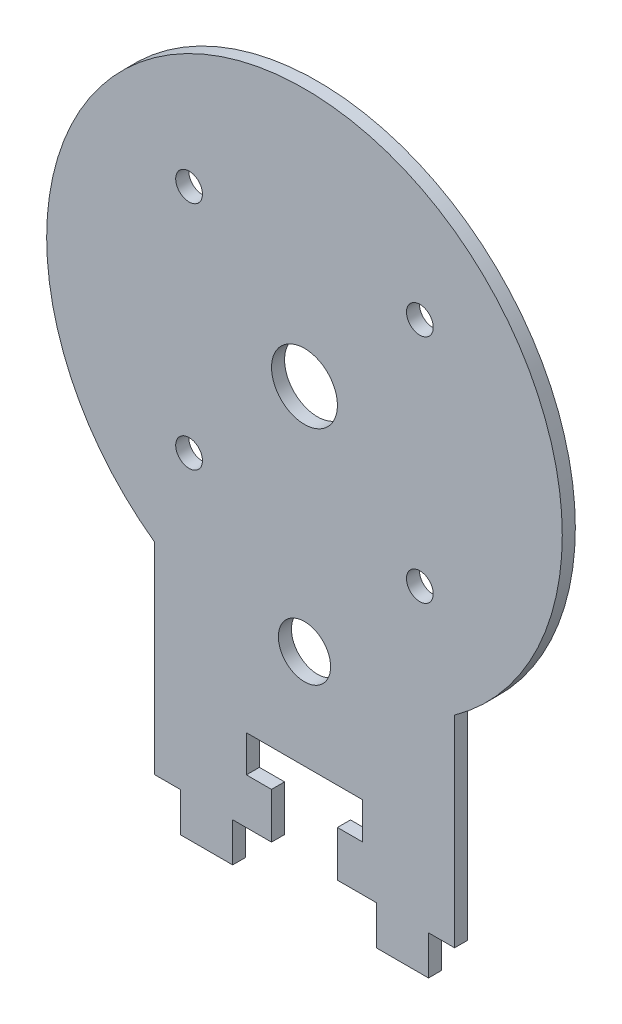
SolidWorks part; units mm, degrees
ref_plane "前视基准面" through (0, 0, 0) normal (0, 0, 1) x (1, 0, 0)
ref_plane "上视基准面" through (0, 0, 0) normal (0, 1, 0) x (1, 0, 0)
ref_plane "右视基准面" through (0, 0, 0) normal (1, 0, 0) x (0, 0, -1)
sketch "草图1" plane through (0, 0, 0) normal (0, 0, 1) x (1, 0, 0)
  line L0 (-7.6377, 83.7363) -> (-7.6377, -1.0167) construction
  line L1 (-48.6877, 98.7363) -> (33.4123, 98.7363) construction
  line L2 (-2.5877, 20.7363) -> (-2.5877, 27.7363)
  line L5 (-2.5877, 27.7363) -> (1.2623, 27.7363)
  line L6 (1.2623, 27.7363) -> (1.2623, 33.3363)
  line L10 (-7.6377, 83.7363) -> (29.2367, 46.8619) construction
  line L11 (1.2623, 33.3363) -> (-2.6877, 33.3363)
  line L15 (3.3623, 20.7363) -> (3.3623, 14.7363)
  line L16 (3.3623, 14.7363) -> (11.3623, 14.7363)
  line L17 (11.3623, 14.7363) -> (11.3623, 20.7363)
  line L18 (7.3623, 14.7363) -> (7.3623, 20.7363) construction
  line L19 (11.3623, 20.7363) -> (-2.5877, 20.7363) construction
  line L20 (-2.5877, 20.7363) -> (3.3623, 20.7363)
  line L21 (11.3623, 20.7363) -> (15.3623, 20.7363)
  line L25 (-26.6377, 20.7363) -> (-12.6877, 20.7363) construction
  line L26 (-22.6377, 14.7363) -> (-22.6377, 20.7363) construction
  line L28 (-26.6377, 20.7363) -> (-30.6377, 20.7363)
  line L29 (-12.6877, 20.7363) -> (-18.6377, 20.7363)
  line L30 (-26.6377, 14.7363) -> (-26.6377, 20.7363)
  line L31 (-18.6377, 14.7363) -> (-26.6377, 14.7363)
  line L32 (-18.6377, 20.7363) -> (-18.6377, 14.7363)
  line L34 (-16.5377, 33.3363) -> (-12.5877, 33.3363)
  line L35 (-16.5377, 27.7363) -> (-16.5377, 33.3363)
  line L36 (-12.6877, 27.7363) -> (-16.5377, 27.7363)
  line L37 (-12.6877, 20.7363) -> (-12.6877, 27.7363)
  line L38 (-30.6377, 20.7363) -> (-30.6377, 51.6232)
  line L39 (15.3623, 20.7363) -> (15.3623, 51.6232)
  line L40 (-12.5877, 33.3363) -> (-2.6877, 33.3363)
  circle A0 centre (-7.6377, 83.7363) radius 5.05
  circle A1 centre (-7.6377, 83.7363) radius 25 construction
  circle A4 centre (-7.6377, 83.7363) radius 20 construction
  circle A8 centre (10.0399, 66.0586) radius 2.05
  circle A10 centre (-7.6377, 38.0045) radius 3.7839 construction
  circle A11 centre (-7.6377, 83.7363) radius 39.5 construction
  arc A12 (-30.6377, 51.6232) -> (15.3623, 51.6232) centre (-7.6377, 83.7363) cw
  circle A19 centre (-25.3154, 66.0586) radius 2.05
  circle A20 centre (-25.3154, 101.4139) radius 2.05
  circle A21 centre (10.0399, 101.4139) radius 2.05
  circle A22 centre (-7.6377, 44.2336) radius 4 construction
  circle A23 centre (-7.6377, 48.5363) radius 4
  point P39 (-7.6377, 43.5363)
  dimension "D1" = 10.1
  dimension "D2" = 50
  dimension "D3" = 4.1
  dimension "D15" = 79
  dimension "D17" = 8
  dimension "D18" = 8
  dimension "D4" = 15
  dimension "D5" = 5.6
  dimension "D6" = 7
  dimension "D7" = 5.05
  dimension "D8" = 8.9
  dimension "D9" = 15
  dimension "D10" = 6
  dimension "D11" = 4
  dimension "D12" = 45
  dimension "D13" = 8
  dimension "D14" = 63
  dimension "D19" = 5
  dimension "D16" = 4
extrude "凸台-拉伸1" add sketch "草图1" along normal blind 2
sketch "草图2" plane through (0, 20.7363, 0) normal (0, -1, 0) x (1, 0, 0)
  line L0 (-12.6877, 1) -> (-2.5877, 1) construction
  line L1 (-12.6877, 2) -> (-12.6877, 0) construction
  line L2 (-2.5877, 2) -> (-2.5877, 0) construction
  circle A0 centre (-7.6377, 1) radius 5.05
